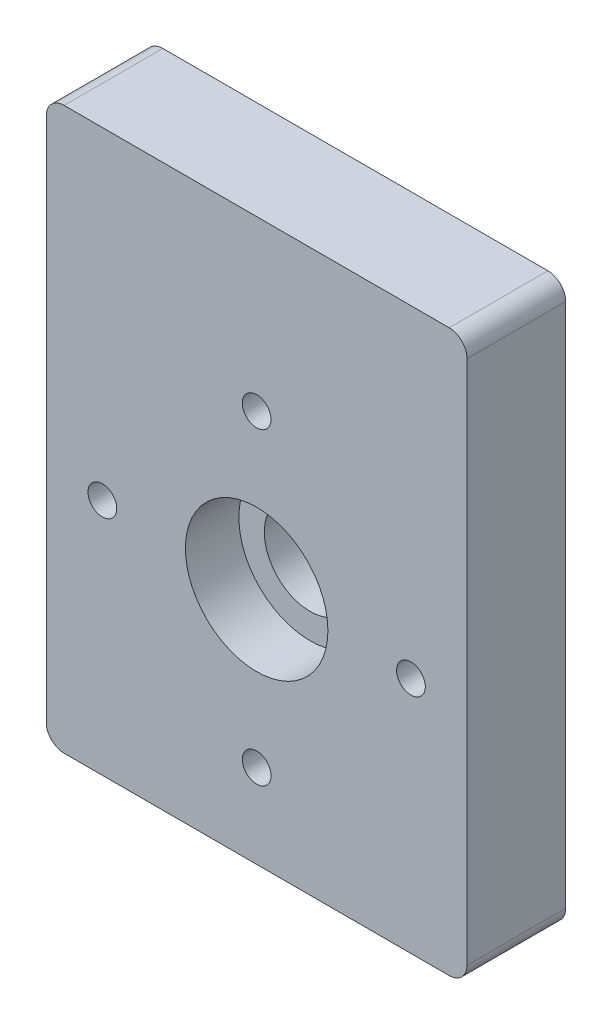
SolidWorks part; units mm, degrees
ref_plane "Front Plane" through (0, 0, 0) normal (0, 0, 1) x (1, 0, 0)
ref_plane "Top Plane" through (0, 0, 0) normal (0, 1, 0) x (1, 0, 0)
ref_plane "Right Plane" through (0, 0, 0) normal (1, 0, 0) x (0, 0, -1)
sketch "Sketch1" plane through (0, 0, 0) normal (0, 0, 1) x (1, 0, 0)
  line L1 (0, 0) -> (30, 0)
  line L2 (0, 0) -> (0, 40)
  line L3 (0, 40) -> (30, 40)
  line L4 (30, 0) -> (30, 40)
  dimension "D1" = 30
  dimension "D2" = 40
extrude "Boss-Extrude1" add sketch "Sketch1" along normal blind 7.0358
hole_wizard "Tap Drill for M2.5x0.45 Tap1" positions "Sketch2" profile "Sketch3" hole size "M2.5x0.45" standard "ANSI Metric" end condition through all
sketch "Sketch2" plane through (0, 0, 7.0358) normal (0, 0, 1) x (1, 0, 0)
  point P0 (15, 27.98)
  point P3 (26, 16.98)
  point P6 (15, 5.98)
  point P9 (4, 16.98)
sketch "Sketch3" plane through (15, 27.98, 7.0358) normal (1, 0, 0) x (0, -1, 0)
  line L0 (0, 0) -> (0, 7.0358)
  line L1 (0, 7.0358) -> (1.025, 7.0358)
  line L2 (1.025, 7.0358) -> (1.025, 0)
  line L5 (1.025, 0) -> (0, 0)
  line L11 (0, -6.35) -> (0, 107.95) construction
  dimension "Thru Hole Dia." = 2.05
  dimension "Thru Hole Depth" = 7.0358
hole_wizard "CBORE for 1/4 Socket Head Cap Screw1" positions "Sketch8" profile "Sketch10" counterbore size "1/4" standard "ANSI Inch" end condition through all
sketch "Sketch8" plane through (0, 0, 7.0358) normal (0, 0, 1) x (1, 0, 0)
  line L0 (4, 16.98) -> (26, 16.98) construction
  point P6 (15, 16.98)
sketch "Sketch10" plane through (15, 16.98, 7.0358) normal (1, 0, 0) x (0, -1, 0)
  line L0 (0, 0) -> (0, 7.0358)
  line L1 (0, 7.0358) -> (3.2639, 7.0358)
  line L3 (3.2639, 7.0358) -> (3.2639, 3.81)
  line L4 (3.2639, 3.81) -> (5.08, 3.81)
  line L5 (5.08, 3.81) -> (5.08, 0)
  line L7 (5.08, 0) -> (0, 0)
  line L11 (0, -6.35) -> (0, 107.95) construction
  dimension "Thru Hole Dia." = 6.5278
  dimension "Thru Hole Depth" = 7.0358
  dimension "C'Bore Dia." = 10.16
  dimension "C'Bore Depth" = 3.81
fillet "Fillet1" radius 1.27 4 edges at (30, 0, 3.5179) (0, 0, 3.5179) (0, 40, 3.5179) (30, 40, 3.5179)
